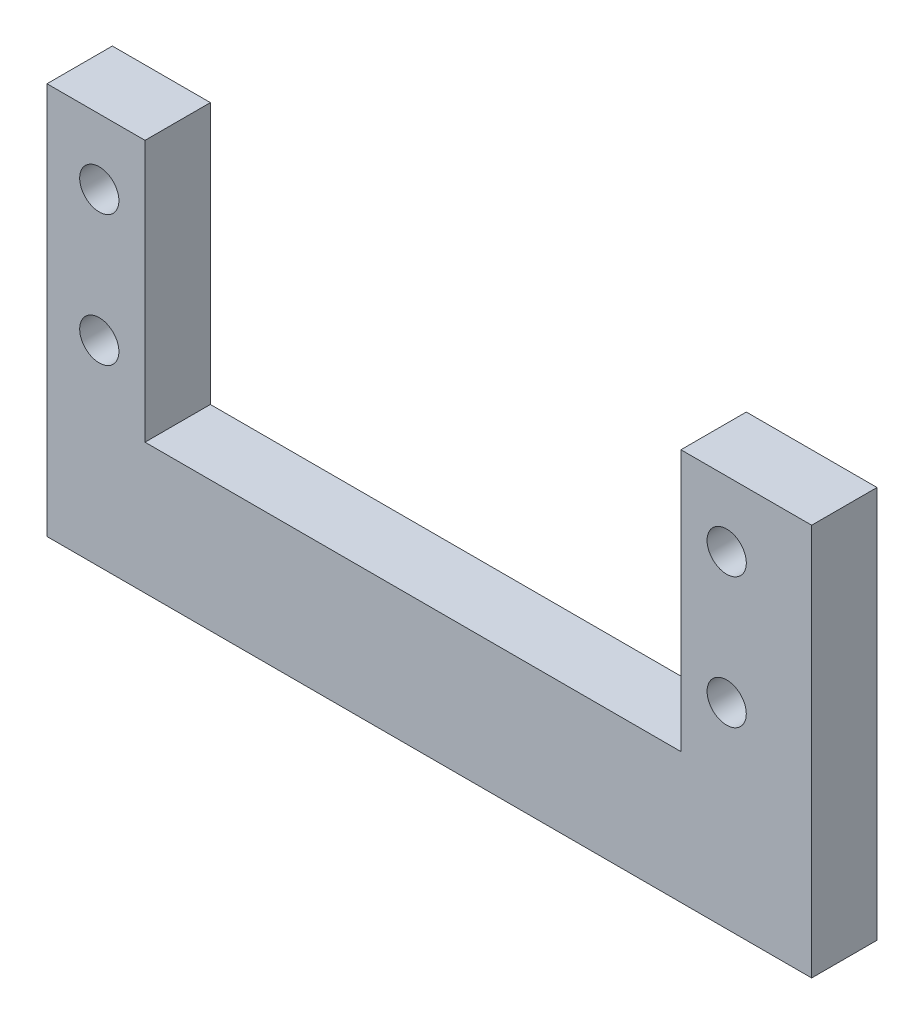
SolidWorks part; units mm, degrees
ref_plane "Plan de face" through (0, 0, 0) normal (0, 0, 1) x (1, 0, 0)
ref_plane "Plan de dessus" through (0, 0, 0) normal (0, 1, 0) x (1, 0, 0)
ref_plane "Plan de droite" through (0, 0, 0) normal (1, 0, 0) x (0, 0, -1)
sketch "Esquisse1" plane through (0, 0, 0) normal (0, 0, 1) x (1, 0, 0)
  line L0 (48.5, 30) -> (58.5, 30)
  line L1 (0, 0) -> (58.5, 0)
  line L2 (0, 0) -> (0, 30)
  line L3 (0, 30) -> (7.5, 30)
  line L4 (58.5, 0) -> (58.5, 30)
  line L5 (7.5, 20) -> (48.5, 20) construction
  line L6 (7.5, 30) -> (7.5, 10)
  line L7 (7.5, 10) -> (48.5, 10)
  line L8 (48.5, 30) -> (48.5, 10)
  line L9 (28, 10) -> (28, 30) construction
  circle A0 centre (4, 25) radius 1.5
  circle A1 centre (4, 15) radius 1.5
  circle A2 centre (52, 15) radius 1.5
  circle A3 centre (52, 25) radius 1.5
  dimension "D6" = 3
  dimension "D8" = 3.5
  dimension "D1" = 20
  dimension "D2" = 7.5
  dimension "D3" = 10
  dimension "D4" = 10
  dimension "D5" = 41
  dimension "D7" = 5
extrude "Boss.-Extru.1" add sketch "Esquisse1" along normal blind 5
